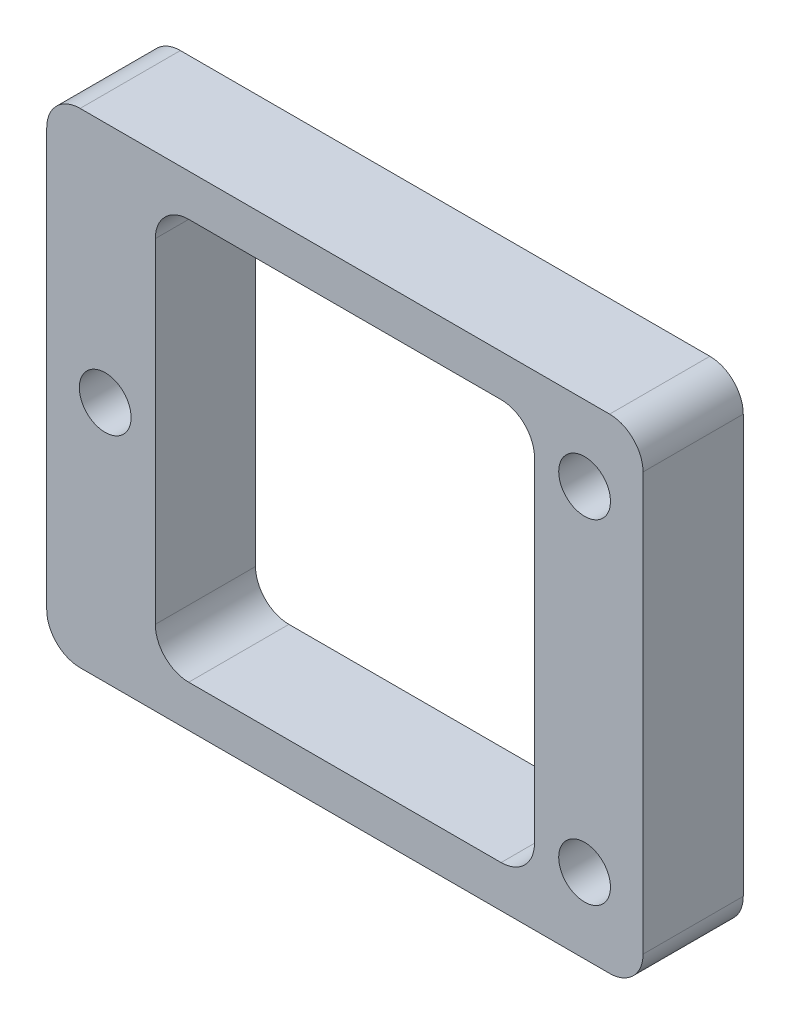
SolidWorks part; units mm, degrees
material "环氧玻璃布层压板"
ref_plane "前视基准面" through (0, 0, 0) normal (0, 0, 1) x (1, 0, 0)
ref_plane "上视基准面" through (0, 0, 0) normal (0, 1, 0) x (1, 0, 0)
ref_plane "右视基准面" through (0, 0, 0) normal (1, 0, 0) x (0, 0, -1)
sketch "草图1" plane through (0, 0, 0) normal (0, 0, 1) x (1, 0, 0)
  line L1 (-17.85, -14.5) -> (17.85, -14.5)
  line L2 (-17.85, -14.5) -> (-17.85, 14.5)
  line L3 (-17.85, 14.5) -> (17.85, 14.5)
  line L4 (17.85, -14.5) -> (17.85, 14.5)
  line L5 (0, 14.5) -> (0, -14.5) construction
  line L6 (-17.85, 0) -> (17.85, 0) construction
  point P0 (0, 0)
  dimension "D1" = 29
  dimension "D2" = 35.7
extrude "凸台-拉伸1" add sketch "草图1" along normal blind 6
sketch "草图2" plane through (0, 0, 0) normal (0, 0, -1) x (-1, 0, 0)
  circle A0 centre (14.35, 0) radius 1.5 construction
  circle A1 centre (-14.35, -10) radius 1.5 construction
  circle A2 centre (-14.35, 10) radius 1.5 construction
  circle A3 centre (14.35, 0) radius 1.5 construction
  circle A4 centre (-14.35, -10) radius 1.5 construction
  circle A5 centre (-14.35, 10) radius 1.5 construction
  circle A6 centre (14.35, 0) radius 1.55
  circle A7 centre (-14.35, 10) radius 1.55
  circle A8 centre (-14.35, -10) radius 1.55
  dimension "D1" = 3.1
extrude "切除-拉伸1" cut sketch "草图2" against normal blind 6
sketch "草图3" plane through (0, 0, 0) normal (0, 0, -1) x (-1, 0, 0)
  line L0 (-17.85, 14.5) -> (17.85, 14.5) construction
  line L1 (-11.35, -12) -> (11.35, -12)
  line L2 (-11.35, -12) -> (-11.35, 12)
  line L3 (-11.35, 12) -> (11.35, 12)
  line L4 (11.35, -12) -> (11.35, 12)
  line L5 (0, 12) -> (0, -12) construction
  line L6 (-11.35, 0) -> (11.35, 0) construction
  circle A0 centre (14.35, 0) radius 1.55 construction
  point P0 (0, 0)
  dimension "D1" = 3
  dimension "D2" = 2.5
extrude "切除-拉伸2" cut sketch "草图3" against normal blind 10
fillet "圆角1" radius 2 8 edges at (17.85, -14.5, 3) (-17.85, -14.5, 3) (11.35, -12, 3) (11.35, 12, 3) (-11.35, 12, 3) (-11.35, -12, 3) (-17.85, 14.5, 3) (17.85, 14.5, 3)
